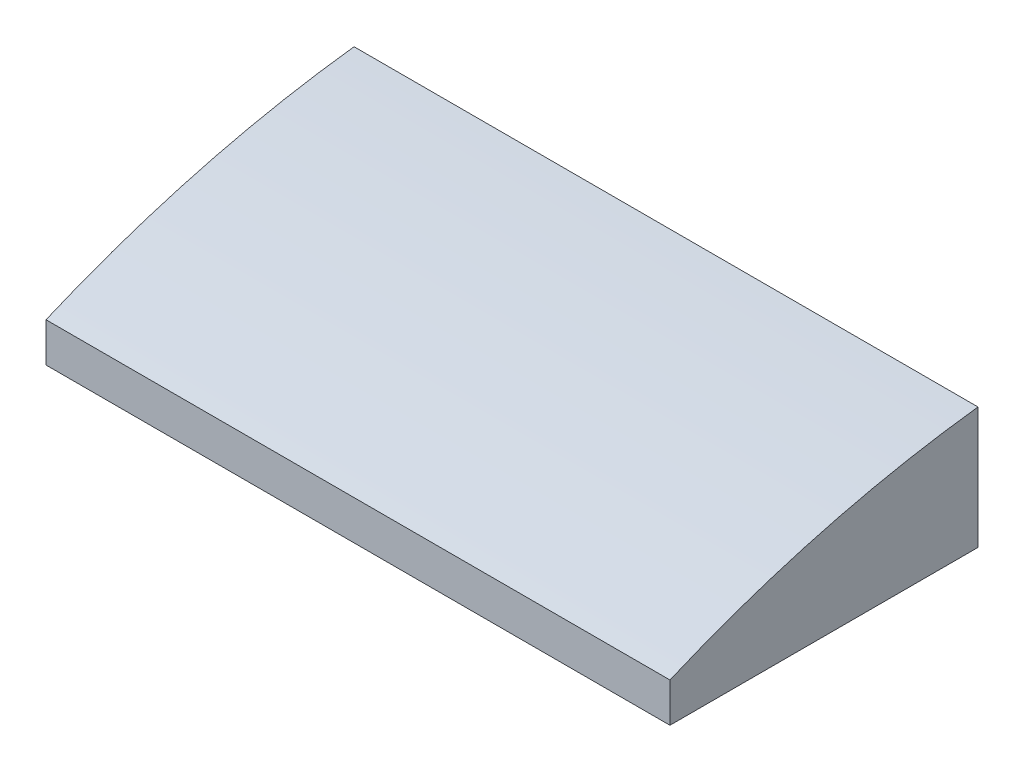
SolidWorks part; units mm, degrees
material "ABS"
ref_plane "Front Plane" through (0, 0, 0) normal (0, 0, 1) x (1, 0, 0)
ref_plane "Top Plane" through (0, 0, 0) normal (0, 1, 0) x (1, 0, 0)
ref_plane "Right Plane" through (0, 0, 0) normal (1, 0, 0) x (0, 0, -1)
sketch "Sketch1" plane through (0, 0, 0) normal (1, 0, 0) x (0, 0, -1)
  line L0 (-7.85, 0) -> (7.85, 0)
  line L1 (7.85, 0) -> (7.85, 6.2)
  line L2 (-7.85, 0) -> (-7.85, 2)
  arc A1 (-7.85, 2) -> (7.85, 6.2) centre (14.841, -51.3771) cw
  point P6 (0, 0)
  dimension "D4" = 58
  dimension "D1" = 15.7
  dimension "D2" = 6.2
  dimension "D3" = 2
extrude "Boss-Extrude1" add sketch "Sketch1" against normal blind 31.8
sketch "Sketch2" plane through (0, 0, 0) normal (0, -1, 0) x (1, 0, 0)
  line L0 (-1.2, 6.65) -> (-1.2, -6.65)
  line L1 (-1.2, -6.65) -> (-30.6, -6.65)
  line L2 (-30.6, -6.65) -> (-30.6, 6.65)
  line L3 (-30.6, 6.65) -> (-1.2, 6.65)
  line L4 (-31.8, -7.85) -> (0, -7.85) construction
  line L5 (0, 7.85) -> (0, -7.85) construction
  line L6 (-31.8, 7.85) -> (0, 7.85) construction
  line L7 (-31.8, 7.85) -> (-31.8, -7.85) construction
  dimension "D1" = 1.2
  dimension "D2" = 1.2
  dimension "D3" = 1.2
  dimension "D4" = 1.2
extrude "Cut-Extrude1" cut sketch "Sketch2" against normal offset from surface (1.74 mm away) 0.7
sketch "Sketch3" plane through (0, 0, 0) normal (0, -1, 0) x (1, 0, 0)
  line L1 (-30.6, -6.65) -> (-1.2, -6.65) construction
  circle A0 centre (-15.9, 0) radius 3.25
  circle A1 centre (-15.9, 0) radius 2.4
  point P8 (-15.9, -6.65)
  dimension "D1" = 4.8
  dimension "D2" = 6.5
extrude "Boss-Extrude2" add sketch "Sketch3" against normal up to surface (4.7383 mm away)
sketch "Sketch4" plane through (0, 0, 0) normal (0, -1, 0) x (1, 0, 0)
  circle A0 centre (-15.9, 0) radius 2.4 construction
  circle A1 centre (-15.9, 0) radius 3.25
  circle A2 centre (-15.9, 0) radius 3.25
  circle A3 centre (-15.9, 0) radius 2.4
  dimension "D1" = 0
extrude "Cut-Extrude2" cut sketch "Sketch4" against normal blind 0.2
pattern_linear "LPattern1" count 2 spacing 8 along (1, 0, 0) of "Boss-Extrude2", "Cut-Extrude2"
pattern_linear "LPattern2" count 2 spacing 8 along (-1, 0, 0) of "Boss-Extrude2", "Cut-Extrude2"
ref_plane "Plane1" through (0, 2, 0) normal (0, -1, 0) x (-1, 0, 0)
sketch "Sketch5" plane through (0, 2, 0) normal (0, -1, 0) x (-1, 0, 0)
  line L0 (30.6, -4.15) -> (1.2, -4.15)
  line L1 (1.2, -6.65) -> (30.6, -6.65) construction
  line L2 (1.2, 6.65) -> (1.2, -6.65) construction
  line L3 (30.6, 6.65) -> (30.6, -6.65) construction
  line L4 (1.2, -6.65) -> (30.6, -6.65)
  line L5 (30.6, -6.65) -> (30.6, -4.15)
  line L6 (1.2, -4.15) -> (1.2, -6.65)
  dimension "D1" = 2.5
extrude "Cut-Extrude3" cut sketch "Sketch5" against normal blind 0.3
